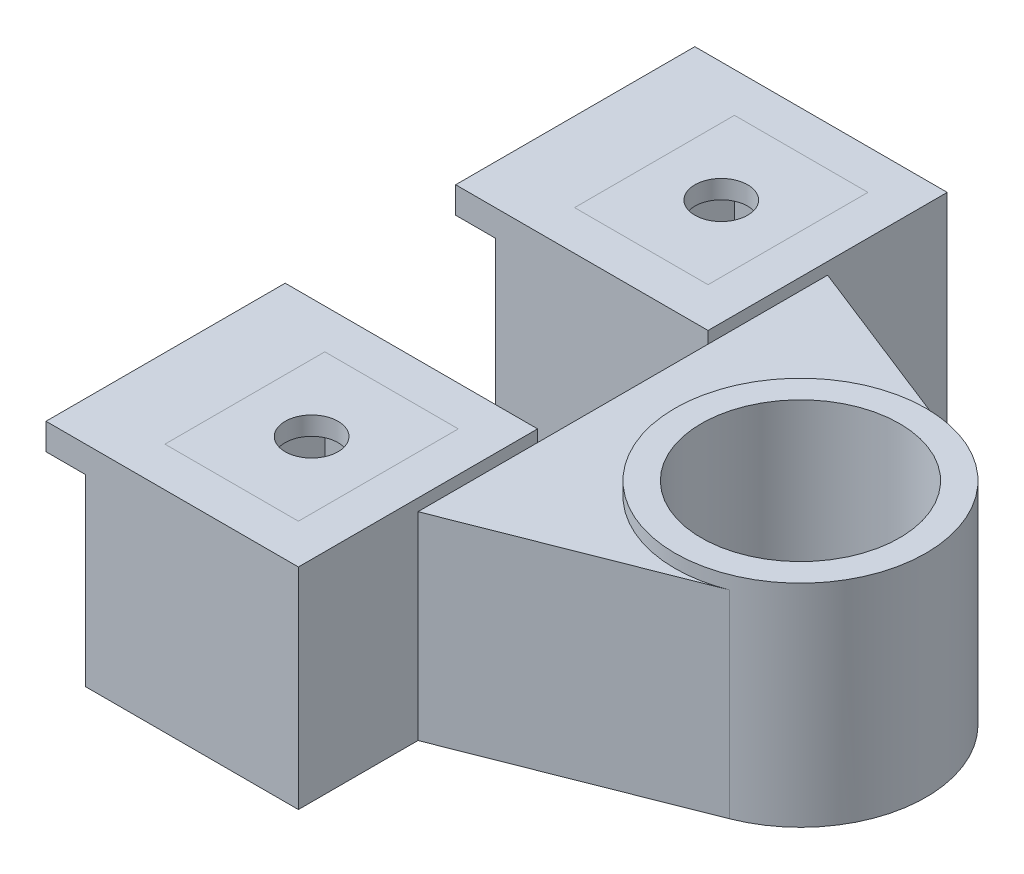
SolidWorks part; units mm, degrees
ref_plane "Front" through (0, 0, 0) normal (0, 0, 1) x (1, 0, 0)
ref_plane "Top" through (0, 0, 0) normal (0, 1, 0) x (1, 0, 0)
ref_plane "Right" through (0, 0, 0) normal (1, 0, 0) x (0, 0, -1)
sketch "Эскиз1" plane through (0, 0, 0) normal (0, 1, 0) x (1, 0, 0)
  circle A0 centre (0, 0) radius 2.5
  dimension "D1" = 5
extrude "Бобышка-Вытянуть1" add sketch "Эскиз1" along normal blind 5
sketch "Эскиз2" plane through (0, 0, 0) normal (0, 1, 0) x (1, 0, 0)
  circle A0 centre (0, 0) radius 9.5
  dimension "D1" = 19
extrude "Бобышка-Вытянуть2" add sketch "Эскиз2" against normal blind 16
sketch "Эскиз3" plane through (0, -16, 0) normal (0, -1, 0) x (1, 0, 0)
  line L0 (-2.6269, 1.5) -> (2.6269, 1.5)
  circle A0 centre (0, 0) radius 3.025
  dimension "D1" = 6.05
  dimension "D2" = 1.5
extrude "Вырез-Вытянуть1" cut sketch "Эскиз3" against normal blind 13.5 contours L0 A0
sketch "Эскиз4" plane through (0, -16, 0) normal (0, -1, 0) x (1, 0, 0)
  circle A0 centre (0, 0) radius 3.025
  dimension "D1" = 6.05
extrude "Вырез-Вытянуть2" cut sketch "Эскиз4" against normal blind 6.5
sketch "Эскиз5" plane through (0, -16, 0) normal (0, -1, 0) x (1, 0, 0)
  circle A0 centre (0, 0) radius 3.525
  dimension "D1" = 7.05
extrude "Вырез-Вытянуть3" cut sketch "Эскиз5" against normal blind 4.5
sketch "Эскиз6" plane through (0, -16, 0) normal (0, -1, 0) x (1, 0, 0)
  line L0 (0, 0) -> (-21.4942, -15.5) construction
  line L1 (0, 0) -> (-26.5, 0) construction
  line L2 (0, 0) -> (-21.4942, 15.5) construction
  line L4 (-39.1652, -2.5) -> (-9.1652, -2.5)
  line L5 (-39.1652, -2.5) -> (-39.1652, 2.5)
  line L6 (-39.1652, 2.5) -> (-9.1652, 2.5)
  line L7 (-9.1652, -2.5) -> (-9.1652, 2.5)
  line L8 (-26.5442, -21.55) -> (-16.4442, -21.55)
  line L9 (-26.5442, -21.55) -> (-26.5442, -9.45)
  line L10 (-26.5442, -9.45) -> (-16.4442, -9.45)
  line L11 (-16.4442, -21.55) -> (-16.4442, -9.45)
  line L12 (-26.5442, -21.55) -> (-16.4442, -9.45) construction
  line L13 (-26.5442, -9.45) -> (-16.4442, -21.55) construction
  line L14 (-26.5442, 9.45) -> (-16.4442, 9.45)
  line L15 (-26.5442, 9.45) -> (-26.5442, 21.55)
  line L16 (-26.5442, 21.55) -> (-16.4442, 21.55)
  line L17 (-16.4442, 9.45) -> (-16.4442, 21.55)
  line L18 (-26.5442, 9.45) -> (-16.4442, 21.55) construction
  line L19 (-26.5442, 21.55) -> (-16.4442, 9.45) construction
  line L20 (-29.5442, -24.55) -> (-13.4442, -24.55)
  line L21 (-29.5442, -24.55) -> (-29.5442, -6.45)
  line L22 (-29.5442, -6.45) -> (-13.4442, -6.45)
  line L23 (-13.4442, -24.55) -> (-13.4442, -6.45)
  line L24 (-29.5442, -24.55) -> (-13.4442, -6.45) construction
  line L25 (-29.5442, -6.45) -> (-13.4442, -24.55) construction
  line L26 (-29.5442, 6.45) -> (-13.4442, 6.45)
  line L27 (-29.5442, 6.45) -> (-29.5442, 24.55)
  line L28 (-29.5442, 24.55) -> (-13.4442, 24.55)
  line L29 (-13.4442, 6.45) -> (-13.4442, 24.55)
  line L30 (-29.5442, 6.45) -> (-13.4442, 24.55) construction
  line L31 (-29.5442, 24.55) -> (-13.4442, 6.45) construction
  circle A0 centre (0, 0) radius 15 construction
  circle A1 centre (0, 0) radius 26.5 construction
  circle A2 centre (-21.4942, -15.5) radius 11.5 construction
  circle A3 centre (-21.4942, 15.5) radius 11.5 construction
  circle A4 centre (0, 0) radius 9.5 construction
  dimension "D1" = 30
  dimension "D2" = 53
  dimension "D3" = 23
  dimension "D5" = 5
  dimension "D4" = 31
  dimension "D6" = 30
  dimension "D7" = 12.1
  dimension "D8" = 10.1
  dimension "D9" = 3
  dimension "D10" = 3
extrude "Бобышка-Вытянуть3" add sketch "Эскиз6" against normal up to surface (16 mm away) separate body contours L20 L23 L22 L21 L11 L8 L9 L10 | L26 L29 L28 L27 L17 L14 L15 L16 up to face at (0, 0, 2.5)
sketch "Эскиз7" plane through (0, 0, 0) normal (0, 1, 0) x (1, 0, 0)
  line L0 (-21.4942, 21.55) -> (-21.4942, -21.55) construction
  line L1 (-26.5442, 21.55) -> (-16.4442, 21.55)
  line L2 (-26.5442, 21.55) -> (-26.5442, 9.45)
  line L3 (-26.5442, 9.45) -> (-16.4442, 9.45)
  line L4 (-16.4442, 21.55) -> (-16.4442, 9.45)
  line L5 (-26.5442, -9.45) -> (-16.4442, -9.45)
  line L6 (-26.5442, -9.45) -> (-26.5442, -21.55)
  line L7 (-26.5442, -21.55) -> (-16.4442, -21.55)
  line L8 (-16.4442, -9.45) -> (-16.4442, -21.55)
  line L9 (-26.5442, 15.5) -> (-16.4442, 15.5) construction
  line L10 (-26.5442, -15.5) -> (-16.4442, -15.5) construction
  circle A0 centre (-21.4942, -15.5) radius 2
  circle A1 centre (-21.4942, 15.5) radius 2
  dimension "D1" = 4
extrude "Бобышка-Вытянуть4" add sketch "Эскиз7" against normal blind 1.5 separate body
sketch "Эскиз8" plane through (0, 0, 0) normal (0, 1, 0) x (1, 0, 0)
  line L1 (-29.5442, 24.55) -> (-13.4442, 24.55)
  line L2 (-29.5442, 24.55) -> (-29.5442, 6.45)
  line L3 (-29.5442, 6.45) -> (-13.4442, 6.45)
  line L4 (-13.4442, 24.55) -> (-13.4442, 6.45)
  line L5 (-29.5442, -6.45) -> (-13.4442, -6.45)
  line L6 (-29.5442, -6.45) -> (-29.5442, -24.55)
  line L7 (-29.5442, -24.55) -> (-13.4442, -24.55)
  line L8 (-13.4442, -6.45) -> (-13.4442, -24.55)
extrude "Вырез-Вытянуть4" cut sketch "Эскиз8" against normal blind 0.1
sketch "Эскиз9" plane through (0, -16, 0) normal (0, -1, 0) x (1, 0, 0)
  line L0 (-13.4442, 15.5) -> (3.4789, 8.8401)
  line L1 (-13.4442, 6.45) -> (-13.4442, 24.55) construction
  line L2 (-13.4442, -15.5) -> (3.4789, -8.8401)
  line L3 (-13.4442, -24.55) -> (-13.4442, -6.45) construction
  line L4 (-13.4442, -15.5) -> (-13.4442, 15.5)
  circle A0 centre (0, 0) radius 9.5 construction
  circle A2 centre (0, 0) radius 9.5
  arc A3 (3.4789, 8.8401) -> (3.4789, -8.8401) centre (0, 0) ccw
  dimension "D1" = 0
extrude "Бобышка-Вытянуть5" add sketch "Эскиз9" against normal blind 15
sketch "Эскиз10" plane through (0, -16, 0) normal (0, -1, 0) x (1, 0, 0)
  circle A0 centre (0, 0) radius 7.5
  dimension "D1" = 15
extrude "Вырез-Вытянуть6" cut sketch "Эскиз10" against normal through all
sketch "Эскиз11" plane through (0, -16, 0) normal (0, -1, 0) x (1, 0, 0)
  line L0 (-29.5442, 15.5) -> (-16.4442, 15.5) construction
  line L1 (-29.5442, 6.45) -> (-29.5442, 24.55) construction
  line L2 (-16.4442, 9.45) -> (-16.4442, 21.55) construction
  line L3 (-29.5442, -15.5) -> (-16.4442, -15.5) construction
  line L4 (-29.5442, -24.55) -> (-29.5442, -6.45) construction
  line L5 (-16.4442, -21.55) -> (-16.4442, -9.45) construction
  line L6 (-29.5442, 17.75) -> (-32.5442, 19.5)
  line L7 (-32.5442, 19.5) -> (-32.5442, 11.5)
  line L8 (-32.5442, 11.5) -> (-29.5442, 13.25)
  line L9 (-29.5442, -13.25) -> (-32.5442, -11.5)
  line L10 (-32.5442, -11.5) -> (-32.5442, -19.5)
  line L11 (-32.5442, -19.5) -> (-29.5442, -17.75)
  line L12 (-29.5442, 17.75) -> (-29.5442, 13.25)
  line L13 (-29.5442, -13.25) -> (-29.5442, -17.75)
  dimension "D1" = 3
  dimension "D2" = 4.5
  dimension "D3" = 8
extrude "Бобышка-Вытянуть6" add sketch "Эскиз11" against normal up to surface (15.9 mm away) separate body up to face at (-21.4942, -0.1, -15.5)
sketch "Эскиз12" plane through (-29.5442, 0, 0) normal (-1, 0, 0) x (0, 0, 1)
  line L0 (-6.45, -0.1) -> (-6.45, -16) construction
  line L1 (-24.55, -0.1) -> (-6.45, -0.1)
  line L2 (-24.55, -0.1) -> (-24.55, -2.1)
  line L3 (-24.55, -2.1) -> (-6.45, -2.1)
  line L4 (-6.45, -0.1) -> (-6.45, -2.1)
  line L5 (24.55, -0.1) -> (24.55, -16) construction
  line L6 (6.45, -0.1) -> (24.55, -0.1)
  line L7 (6.45, -0.1) -> (6.45, -2.1)
  line L8 (6.45, -2.1) -> (24.55, -2.1)
  line L9 (24.55, -0.1) -> (24.55, -2.1)
  dimension "D1" = 2
extrude "Бобышка-Вытянуть7" add sketch "Эскиз12" along normal up to surface (3 mm away) up to face at (-32.5442, -8.05, -15.5)
